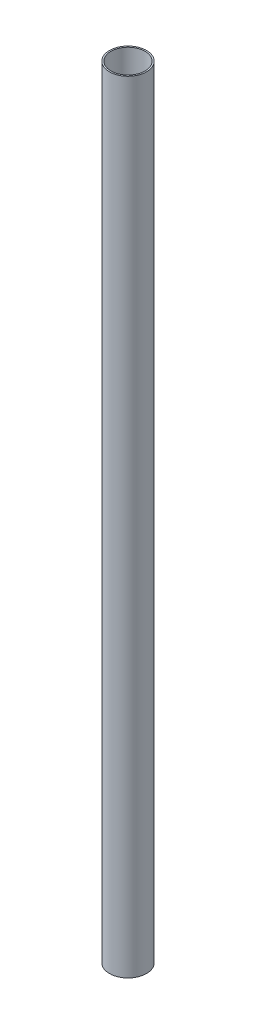
SolidWorks part; units mm, degrees
ref_plane "前视基准面" through (0, 0, 0) normal (0, 0, 1) x (1, 0, 0)
ref_plane "上视基准面" through (0, 0, 0) normal (0, 1, 0) x (1, 0, 0)
ref_plane "右视基准面" through (0, 0, 0) normal (1, 0, 0) x (0, 0, -1)
sketch "草图1" plane through (0, 0, 0) normal (0, 1, 0) x (1, 0, 0)
  circle A0 centre (0, 0) radius 19
  circle A1 centre (0, 0) radius 17.5
  dimension "D1" = 35
  dimension "D2" = 38
extrude "凸台-拉伸1" add sketch "草图1" along normal blind 800
sketch "草图2" plane through (0, 0, 0) normal (1, 0, 0) x (0, 0, -1)
  circle A0 centre (0, 60) radius 4
  circle A1 centre (0, 120) radius 4
  circle A2 centre (0, 180) radius 4
  circle A3 centre (0, 240) radius 4
  dimension "D1" = 8
  dimension "D2" = 8
  dimension "D3" = 8
  dimension "D7" = 8
  dimension "D4" = 60
  dimension "D5" = 60
  dimension "D6" = 60
  dimension "D8" = 60
extrude "切除-拉伸1" cut sketch "草图2" against normal blind 50
